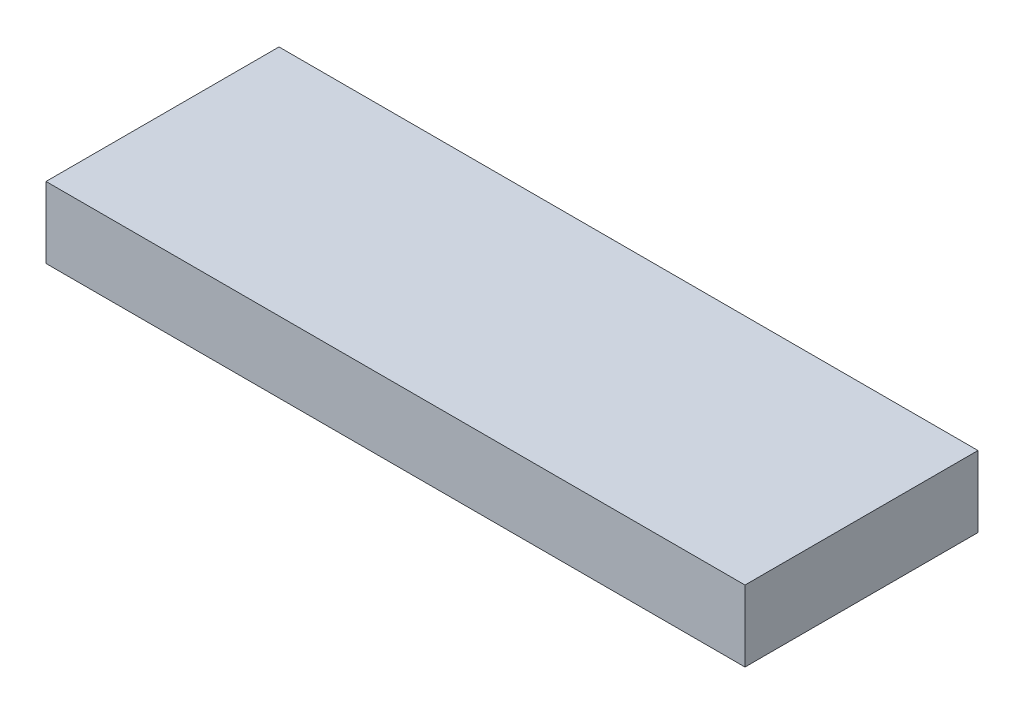
SolidWorks part; units mm, degrees
ref_plane "Front Plane" through (0, 0, 0) normal (0, 0, 1) x (1, 0, 0)
ref_plane "Top Plane" through (0, 0, 0) normal (0, 1, 0) x (1, 0, 0)
ref_plane "Right Plane" through (0, 0, 0) normal (1, 0, 0) x (0, 0, -1)
sketch "Sketch1" plane through (0, 0, 0) normal (0, 1, 0) x (1, 0, 0)
  line L1 (0, 0) -> (76.2, 0)
  line L2 (0, 0) -> (0, 25.4)
  line L3 (0, 25.4) -> (76.2, 25.4)
  line L4 (76.2, 0) -> (76.2, 25.4)
  dimension "D1" = 25.4
  dimension "D2" = 76.2
extrude "Boss-Extrude1" add sketch "Sketch1" along normal blind 7.747
